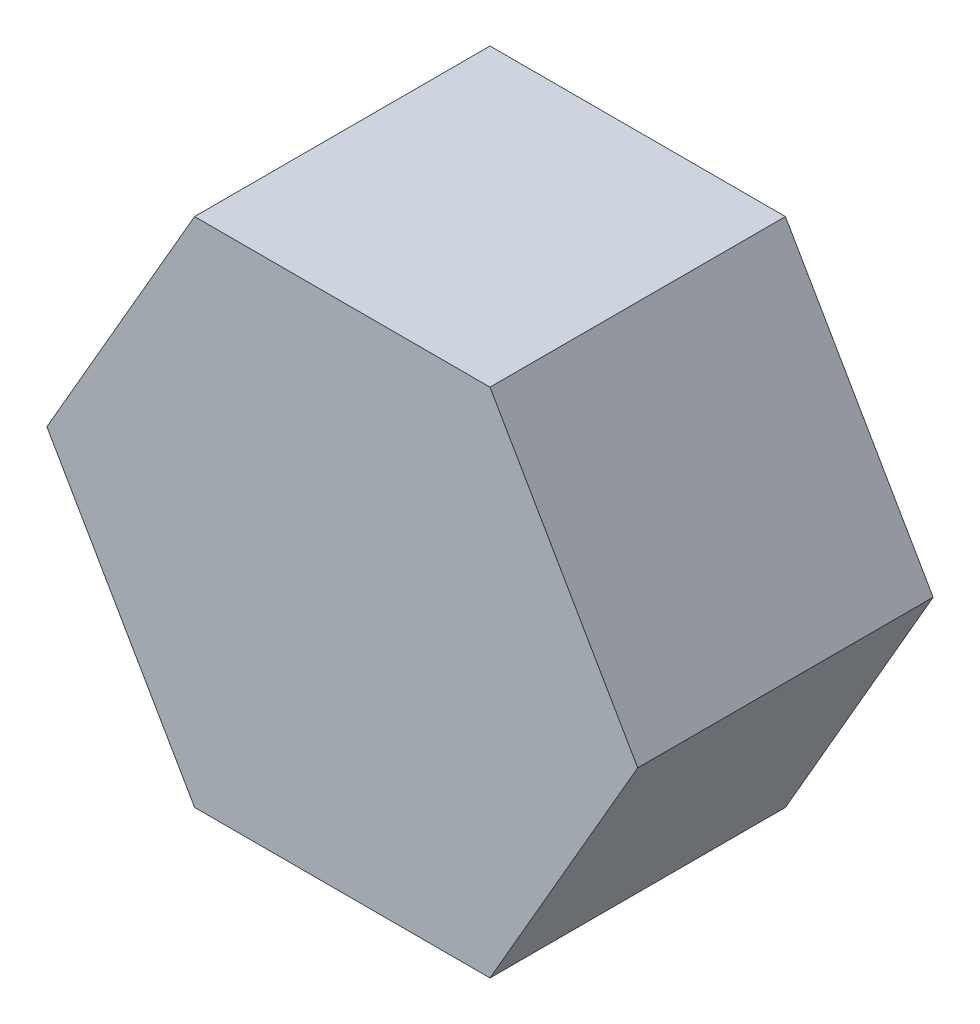
SolidWorks part; units mm, degrees
ref_plane "Front Plane" through (0, 0, 0) normal (0, 0, 1) x (1, 0, 0)
ref_plane "Top Plane" through (0, 0, 0) normal (0, 1, 0) x (1, 0, 0)
ref_plane "Right Plane" through (0, 0, 0) normal (1, 0, 0) x (0, 0, -1)
sketch "Sketch6" plane through (0, 0, 0) normal (0, 0, 1) x (1, 0, 0)
  line L0 (0, 0) -> (25, 0)
  line L1 (0, 0) -> (-12.5, -21.6506)
  line L2 (-12.5, -21.6506) -> (0, -43.3013)
  line L3 (0, -43.3013) -> (25, -43.3013)
  line L4 (25, 0) -> (37.5, -21.6506)
  line L5 (37.5, -21.6506) -> (25, -43.3013)
extrude "Boss-Extrude5" add sketch "Sketch6" along normal blind 25
